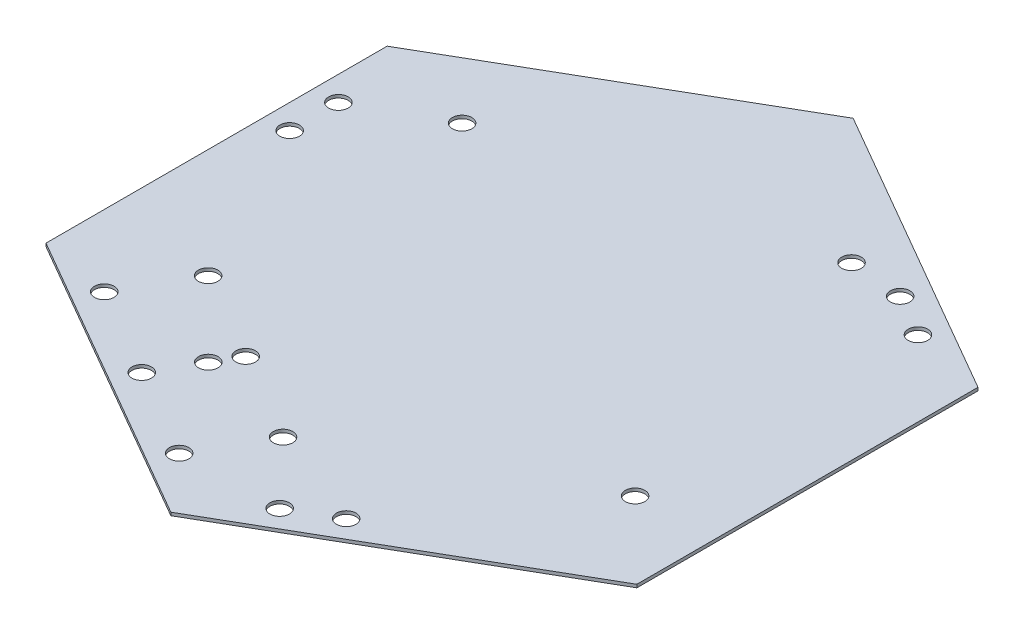
SolidWorks part; units mm, degrees
material "1060 Alloy"
ref_plane "Front Plane" through (0, 0, 0) normal (0, 0, 1) x (1, 0, 0)
ref_plane "Top Plane" through (0, 0, 0) normal (0, 1, 0) x (1, 0, 0)
ref_plane "Right Plane" through (0, 0, 0) normal (1, 0, 0) x (0, 0, -1)
sketch "Sketch1" plane through (0, 0, 0) normal (0, 1, 0) x (1, 0, 0)
  line L0 (13.3228, -73.8757) -> (24.3213, -67.5257) construction
  line L1 (0, 88.9) -> (-76.9897, 44.45)
  line L2 (-76.9897, 44.45) -> (-76.9897, -44.45)
  line L3 (-76.9897, -44.45) -> (0, -88.9)
  line L4 (0, -88.9) -> (76.9897, -44.45)
  line L5 (76.9897, -44.45) -> (76.9897, 44.45)
  line L6 (76.9897, 44.45) -> (0, 88.9)
  line L7 (24.3213, -67.5257) -> (27.4963, -73.025) construction
  line L8 (-70.6397, 12.7) -> (-76.9897, 12.7) construction
  line L9 (-70.6397, 25.4) -> (-70.6397, 12.7) construction
  line L10 (46.3184, 54.8257) -> (49.4934, 60.325) construction
  line L11 (57.3169, 48.4757) -> (46.3184, 54.8257) construction
  line L12 (13.3228, -73.8757) -> (16.4978, -79.375) construction
  circle A0 centre (0, 0) radius 76.9897 construction
  circle A1 centre (13.3228, -73.8757) radius 2.54
  circle A2 centre (24.3213, -67.5257) radius 2.54
  circle A7 centre (-70.6397, 12.7) radius 2.54
  circle A8 centre (-70.6397, 25.4) radius 2.54
  circle A9 centre (46.3184, 54.8257) radius 2.54
  circle A10 centre (57.3169, 48.4757) radius 2.54
  point P13 (38.4948, -66.675)
  point P28 (3.175, -1.8331)
  point P29 (0, 0)
  dimension "D2" = 5.08
  dimension "D3" = 6.35
  dimension "D4" = 12.7
  dimension "D1" = 177.8
  dimension "D5" = 12.7
extrude "Boss-Extrude1" add sketch "Sketch1" along normal blind 0.8128
sketch "Sketch2" plane through (0, 0.8128, 0) normal (0, 1, 0) x (1, 0, 0)
  line L0 (-49.8503, 36.8467) -> (56.8353, -24.7483) construction
  line L1 (27.9428, -74.7916) -> (-78.7428, -13.1966) construction
  line L2 (27.9428, -74.7916) -> (85.7278, 25.295) construction
  line L3 (85.7278, 25.295) -> (-20.9578, 86.89) construction
  line L4 (-78.7428, -13.1966) -> (-20.9578, 86.89) construction
  line L5 (-76.9897, -44.45) -> (0, -88.9) construction
  line L6 (32.385, 56.0925) -> (-25.4, -43.9941) construction
  circle A0 centre (-49.8503, 36.8467) radius 2.54
  circle A1 centre (-25.4, -43.9941) radius 2.54
  circle A2 centre (32.385, 56.0925) radius 2.54
  circle A3 centre (56.8353, -24.7483) radius 2.54
  dimension "D5" = 5.08
  dimension "D6" = 57.785
  dimension "D1" = 123.19
  dimension "D2" = 115.57
  dimension "D3" = 61.595
  dimension "D4" = 50.8
  dimension "D7" = 61.595
extrude "Cut-Extrude1" cut sketch "Sketch2" against normal through all
sketch "Sketch3" plane through (0, 0.8128, 0) normal (0, 1, 0) x (1, 0, 0)
  line L0 (-35.3198, -61.1757) -> (-38.4948, -66.675) construction
  line L2 (-76.9897, -44.45) -> (0, -88.9) construction
  line L5 (-28.9698, -50.1772) -> (-35.3198, -61.1757) construction
  circle A2 centre (-35.3198, -61.1757) radius 2.54
  circle A3 centre (-28.9698, -50.1772) radius 2.54
  point P0 (-38.4948, -66.675)
  dimension "D1" = 5.08
  dimension "D2" = 6.35
  dimension "D4" = 12.7
extrude "Cut-Extrude2" cut sketch "Sketch3" against normal through all
sketch "Sketch5" plane through (0, 0.8128, 0) normal (0, 1, 0) x (1, 0, 0)
  line L0 (-76.9897, -44.45) -> (0, -88.9) construction
  circle A0 centre (-2.3169, -57.353) radius 2.54
  circle A1 centre (-12.2229, -74.5107) radius 2.54
  circle A2 centre (-58.4167, -47.8407) radius 2.54
  circle A3 centre (-48.5107, -30.6831) radius 2.54
  circle A4 centre (-25.4, -43.9941) radius 2.54 construction
  circle A5 centre (-35.3198, -61.1757) radius 2.54 construction
  dimension "D1" = 5.08
  dimension "D2" = 5.08
  dimension "D3" = 5.08
  dimension "D4" = 5.08
  dimension "D5" = 6.35
  dimension "D6" = 6.35
  dimension "D7" = 26.67
  dimension "D8" = 26.67
  dimension "D9" = 26.67
  dimension "D10" = 26.67
  dimension "D11" = 19.812
  dimension "D12" = 19.812
extrude "Cut-Extrude3" cut sketch "Sketch5" against normal blind 2.54
